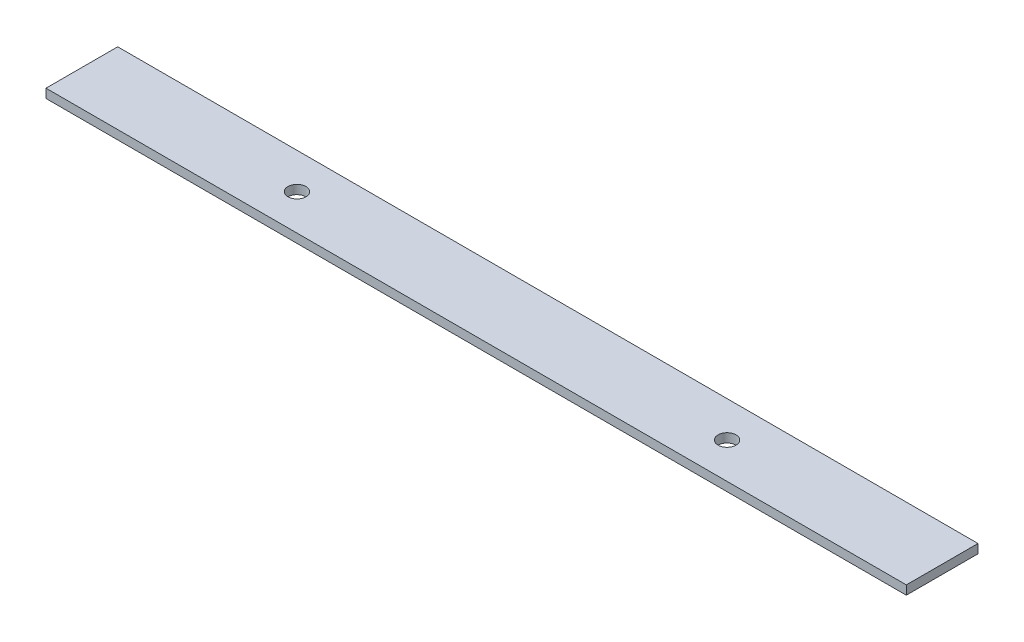
SolidWorks part; units mm, degrees
ref_plane "Front Plane" through (0, 0, 0) normal (0, 0, 1) x (1, 0, 0)
ref_plane "Top Plane" through (0, 0, 0) normal (0, 1, 0) x (1, 0, 0)
ref_plane "Right Plane" through (0, 0, 0) normal (1, 0, 0) x (0, 0, -1)
sketch "Sketch1" plane through (0, 0, 0) normal (0, 1, 0) x (1, 0, 0)
  line L1 (0, 0) -> (304.8, 0)
  line L2 (0, 0) -> (0, -25.4)
  line L3 (0, -25.4) -> (304.8, -25.4)
  line L4 (304.8, 0) -> (304.8, -25.4)
  dimension "D1" = 304.8
  dimension "D2" = 25.4
extrude "Boss-Extrude1" add sketch "Sketch1" along normal blind 3.175
sketch "Sketch2" plane through (0, 3.175, 0) normal (0, 1, 0) x (1, 0, 0)
  line L0 (304.8, 0) -> (0, 0) construction
  line L1 (0, -25.4) -> (304.8, -25.4) construction
  line L2 (152.4, 0) -> (152.4, -25.4) construction
  circle A0 centre (76.2, -12.7) radius 3.175
  circle A1 centre (228.6, -12.7) radius 3.175
  dimension "D1" = 6.35
  dimension "D2" = 25.4
  dimension "D3" = 12.7
  dimension "D4" = 76.2
  dimension "D5" = 152.4
extrude "Cut-Extrude1" cut sketch "Sketch2" against normal up to surface (3.175 mm away) up to face at (152.4, 0, 12.7)
